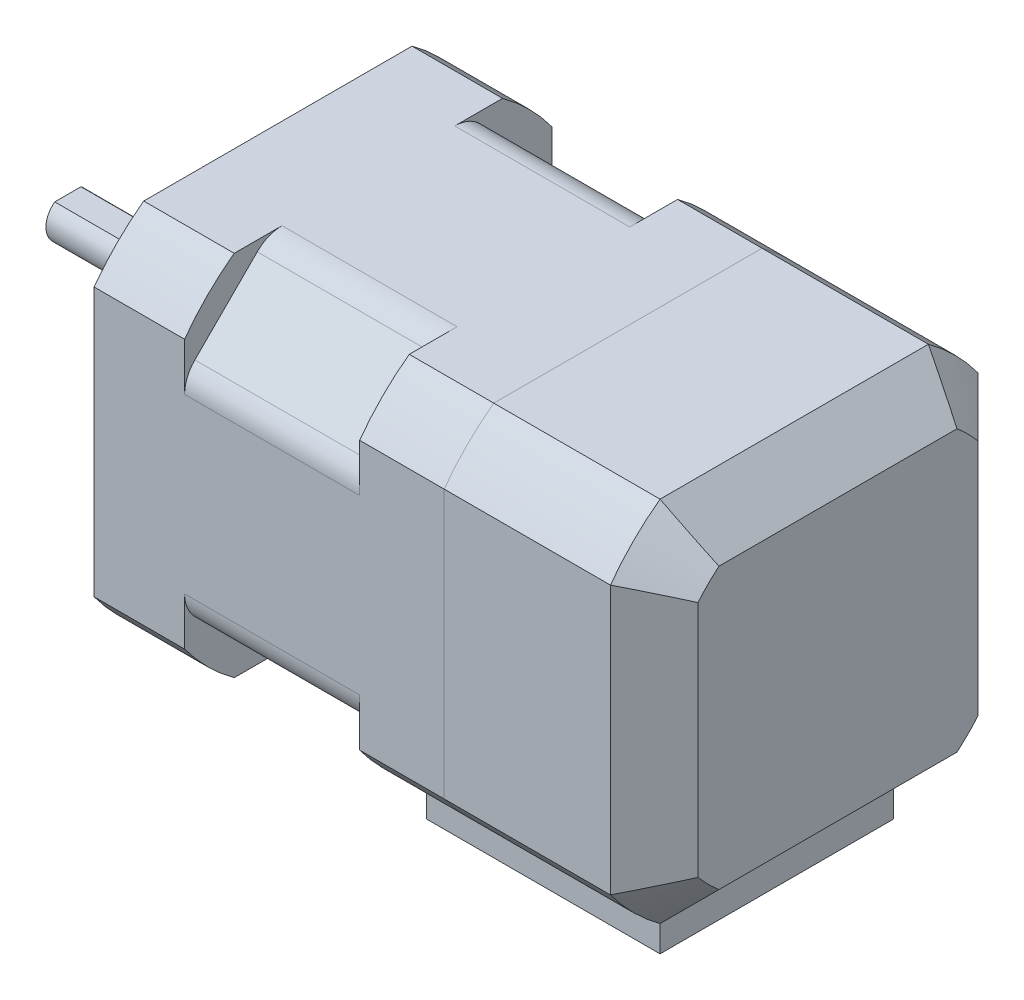
SolidWorks part; units mm, degrees
material "Aluminium"
ref_plane "Plan XY" through (0, 0, 0) normal (0, 0, 1) x (1, 0, 0)
ref_plane "Plan ZX" through (0, 0, 0) normal (0, 1, 0) x (1, 0, 0)
ref_plane "Plan YZ" through (0, 0, 0) normal (1, 0, 0) x (0, 0, -1)
sketch "Esquisse1" plane through (0, 0, 0) normal (1, 0, 0) x (0, 0, -1)
  line L1 (21, -21) -> (-21, -21)
  line L2 (21, -21) -> (21, 21)
  line L3 (21, 21) -> (-21, 21)
  line L4 (-21, -21) -> (-21, 21)
  line L5 (21, -21) -> (-21, 21) construction
  line L6 (21, 21) -> (-21, -21) construction
  point P0 (0, 0)
  dimension "D1" = 42
extrude "Boss.-Extru.1" add sketch "Esquisse1" along normal blind 64
sketch "Esquisse2" plane through (0, 0, 0) normal (1, 0, 0) x (0, 0, -1)
  circle A0 centre (0, 0) radius 11
  dimension "D1" = 22
extrude "Boss.-Extru.2" add sketch "Esquisse2" against normal blind 2
sketch "Esquisse3" plane through (0, 0, 0) normal (-1, 0, 0) x (0, 0, 1)
  circle A0 centre (0, 0) radius 2.5
  dimension "D1" = 5
extrude "Boss.-Extru.3" add sketch "Esquisse3" along normal blind 24
hole_wizard "Trou taraudé M31" positions "Esquisse4" profile "Esquisse5" tap size "M3" standard "ISO"
sketch "Esquisse4" plane through (0, 0, 0) normal (-1, 0, 0) x (0, 0, 1)
  line L1 (15.5, -15.5) -> (-15.5, -15.5) construction
  line L2 (15.5, -15.5) -> (15.5, 15.5) construction
  line L3 (15.5, 15.5) -> (-15.5, 15.5) construction
  line L4 (-15.5, -15.5) -> (-15.5, 15.5) construction
  line L5 (15.5, -15.5) -> (-15.5, 15.5) construction
  line L6 (15.5, 15.5) -> (-15.5, -15.5) construction
  point P0 (-15.5, 15.5)
  point P2 (15.5, 15.5)
  point P4 (-15.5, -15.5)
  point P6 (15.5, -15.5)
  dimension "D1" = 31
sketch "Esquisse5" plane through (0, 15.5, -15.5) normal (0, 1, 0) x (0, 0, 1)
  line L0 (0, 0) -> (0, 4.7511)
  line L1 (0, 4.7511) -> (1.25, 4)
  line L2 (1.25, 4) -> (1.25, 0)
  line L5 (1.25, 0) -> (0, 0)
  line L10 (0, 4.7511) -> (-1.25, 4) construction
  line L11 (0, -6.35) -> (0, 107.95) construction
  dimension "Diamètre du trou pour taraudage" = 2.5
  dimension "Profondeur du trou pour taraudage" = 4
  dimension "Angle de pointe" = 118
cosmetic thread "Filetage de perçage1" parameters "D1"=4, "D2"=3
cosmetic thread "Filetage de perçage2" parameters "D1"=4, "D2"=3
cosmetic thread "Filetage de perçage3" parameters "D1"=4, "D2"=3
cosmetic thread "Filetage de perçage4" parameters "D1"=4, "D2"=3
sketch "Esquisse6" plane through (0, 0, 0) normal (1, 0, 0) x (0, 0, -1)
  circle A0 centre (0, 0) radius 26
  dimension "D1" = 52
extrude "Enlèv. mat.-Extru.1" cut sketch "Esquisse6" along normal through all flip side to cut
sketch "Esquisse7" plane through (0, 0, 0) normal (0, 0, 1) x (1, 0, 0)
  line L0 (-24, 2) -> (-9, 2)
  line L1 (-24, 2.5) -> (-24, -2.5) construction
  line L2 (-9, 2) -> (-9, 2.5)
  line L3 (-2, 2.5) -> (-24, 2.5) construction
  line L4 (-24, -2.5) -> (-2, -2.5) construction
  dimension "D1" = 4.5
  dimension "D2" = 15
extrude "Enlèv. mat.-Extru.2" cut sketch "Esquisse7" against normal through all both and the other way through all
ref_plane "Plan1" through (40, 0, 0) normal (1, 0, 0) x (0, 0, -1)
split line "Ligne de séparation1"
chamfer "Chanfrein1" distance 5 angle 45 8 edges at (64, -21, 0) (64, -18.3848, 18.3848) (64, 0, 21) (64, 18.3848, 18.3848) (64, 21, 0) (64, 18.3848, -18.3848) (64, 0, -21) (64, -18.3848, -18.3848)
sketch "Esquisse10" plane through (0, -21, 0) normal (0, -1, 0) x (1, 0, 0)
  line L0 (40, 15.3297) -> (0, 15.3297) construction
  line L1 (59, -15.3297) -> (28.3406, -15.3297) construction
  line L2 (59, -15.3297) -> (59, 15.3297) construction
  line L3 (59, 15.3297) -> (28.3406, 15.3297) construction
  line L4 (28.3406, -15.3297) -> (28.3406, 15.3297) construction
  line L5 (57, -13.3297) -> (30.3406, -13.3297)
  line L6 (30.3406, -13.3297) -> (30.3406, 13.3297)
  line L7 (57, 13.3297) -> (30.3406, 13.3297)
  line L8 (57, -13.3297) -> (57, 13.3297)
  dimension "D1" = 2
extrude "Boss.-Extru.5" add sketch "Esquisse10" along normal blind 10
chamfer "Chanfrein2" distance 5 angle 45 3 edges at (43.6703, -31, 13.3297) (57, -31, 0) (43.6703, -31, -13.3297)
sketch "Esquisse11" plane through (30.3406, 0, 0) normal (-1, 0, 0) x (0, 0, 1)
  line L0 (0, 32.5269) -> (-32.5269, 0)
  line L1 (0, 32.5269) -> (32.5269, 0)
  line L2 (-32.5269, 0) -> (0, -32.5269)
  line L3 (32.5269, 0) -> (0, -32.5269)
  line L4 (-32.5269, 0) -> (0, 0) construction
  line L5 (0, 0) -> (0, 32.5269) construction
  line L6 (0, -32.5269) -> (0, 0) construction
  dimension "D1" = 46
extrude "Enlèv. mat.-Extru.3" cut sketch "Esquisse11" along normal blind 20 flip side to cut
fillet "Congé1" radius 4 8 edges at (20.3406, -21, 11.5269) (20.3406, -11.5269, 21) (20.3406, 11.5269, 21) (20.3406, 21, 11.5269) (20.3406, 21, -11.5269) (20.3406, 11.5269, -21) (20.3406, -21, -11.5269) (20.3406, -11.5269, -21)
